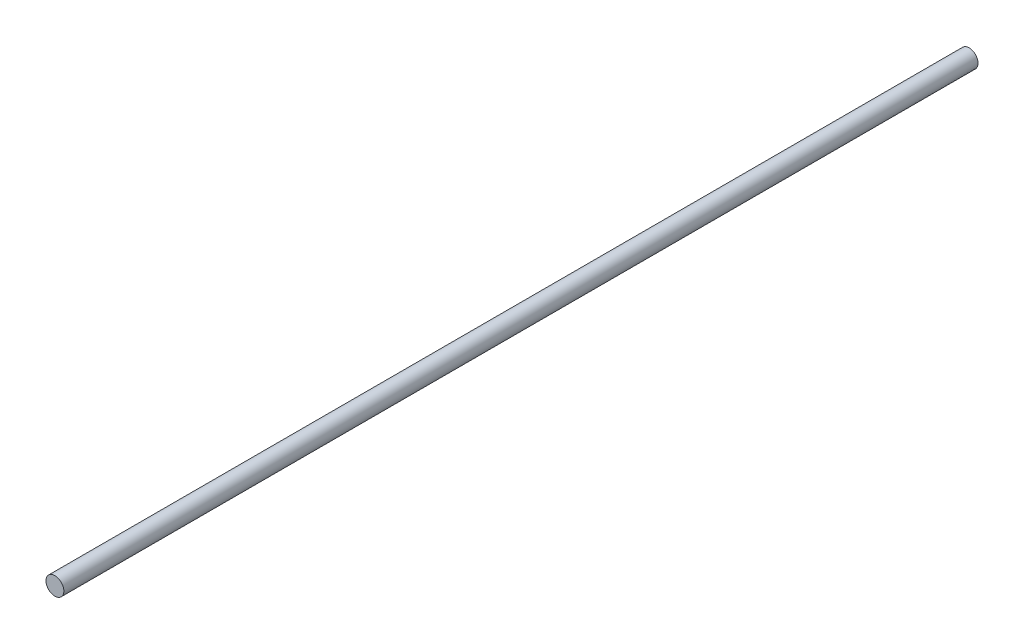
SolidWorks part; units mm, degrees
ref_plane "Front Plane" through (0, 0, 0) normal (0, 0, 1) x (1, 0, 0)
ref_plane "Top Plane" through (0, 0, 0) normal (0, 1, 0) x (1, 0, 0)
ref_plane "Right Plane" through (0, 0, 0) normal (1, 0, 0) x (0, 0, -1)
sketch "Sketch1" plane through (0, 0, 0) normal (0, 0, 1) x (1, 0, 0)
  circle A0 centre (0, 0) radius 6
  circle A1 centre (0, 0) radius 6 construction
extrude "Boss-Extrude1" add sketch "Sketch1" against normal up to surface (615 mm away)
